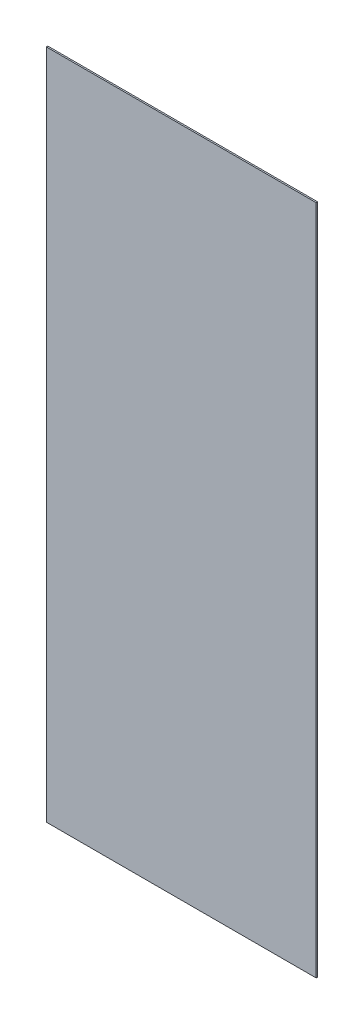
SolidWorks part; units mm, degrees
ref_plane "前基準面" through (0, 0, 0) normal (0, 0, 1) x (1, 0, 0)
ref_plane "上基準面" through (0, 0, 0) normal (0, 1, 0) x (1, 0, 0)
ref_plane "右基準面" through (0, 0, 0) normal (1, 0, 0) x (0, 0, -1)
sketch "草圖1" plane through (0, 0, 0) normal (0, 0, 1) x (1, 0, 0)
  line L1 (-253.15, 629.75) -> (253.15, 629.75)
  line L2 (-253.15, 629.75) -> (-253.15, -629.75)
  line L3 (-253.15, -629.75) -> (253.15, -629.75)
  line L4 (253.15, 629.75) -> (253.15, -629.75)
  line L5 (-253.15, 629.75) -> (253.15, -629.75) construction
  line L6 (-253.15, -629.75) -> (253.15, 629.75) construction
  point P0 (0, 0)
  dimension "D1" = 506.3
  dimension "D2" = 1259.5
extrude "填料-伸長1" add sketch "草圖1" along normal blind 2.75
